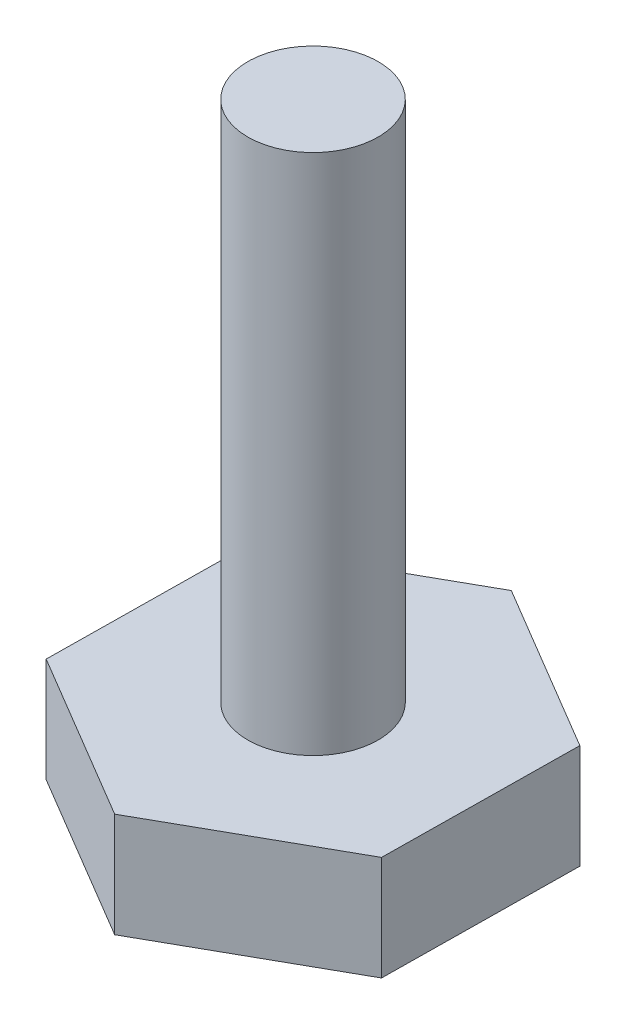
SolidWorks part; units mm, degrees
ref_plane "Front Plane" through (0, 0, 0) normal (0, 0, 1) x (1, 0, 0)
ref_plane "Top Plane" through (0, 0, 0) normal (0, 1, 0) x (1, 0, 0)
ref_plane "Right Plane" through (0, 0, 0) normal (1, 0, 0) x (0, 0, -1)
sketch "Sketch1" plane through (0, 0, 0) normal (0, 1, 0) x (1, 0, 0)
  line L1 (6.4548, -3.8301) -> (6.5443, 3.6749)
  line L2 (6.5443, 3.6749) -> (0.0896, 7.505)
  line L3 (0.0896, 7.505) -> (-6.4548, 3.8301)
  line L4 (-6.4548, 3.8301) -> (-6.5443, -3.6749)
  line L5 (-6.5443, -3.6749) -> (-0.0896, -7.505)
  line L6 (-0.0896, -7.505) -> (6.4548, -3.8301)
  circle A0 centre (0, 0) radius 6.5 construction
  dimension "D1" = 13
extrude "Boss-Extrude1" add sketch "Sketch1" along normal blind 4
sketch "Sketch2" plane through (0, 4, 0) normal (0, 1, 0) x (1, 0, 0)
  circle A0 centre (0, 0) radius 2.5
  dimension "D1" = 5
extrude "Boss-Extrude2" add sketch "Sketch2" along normal blind 20
